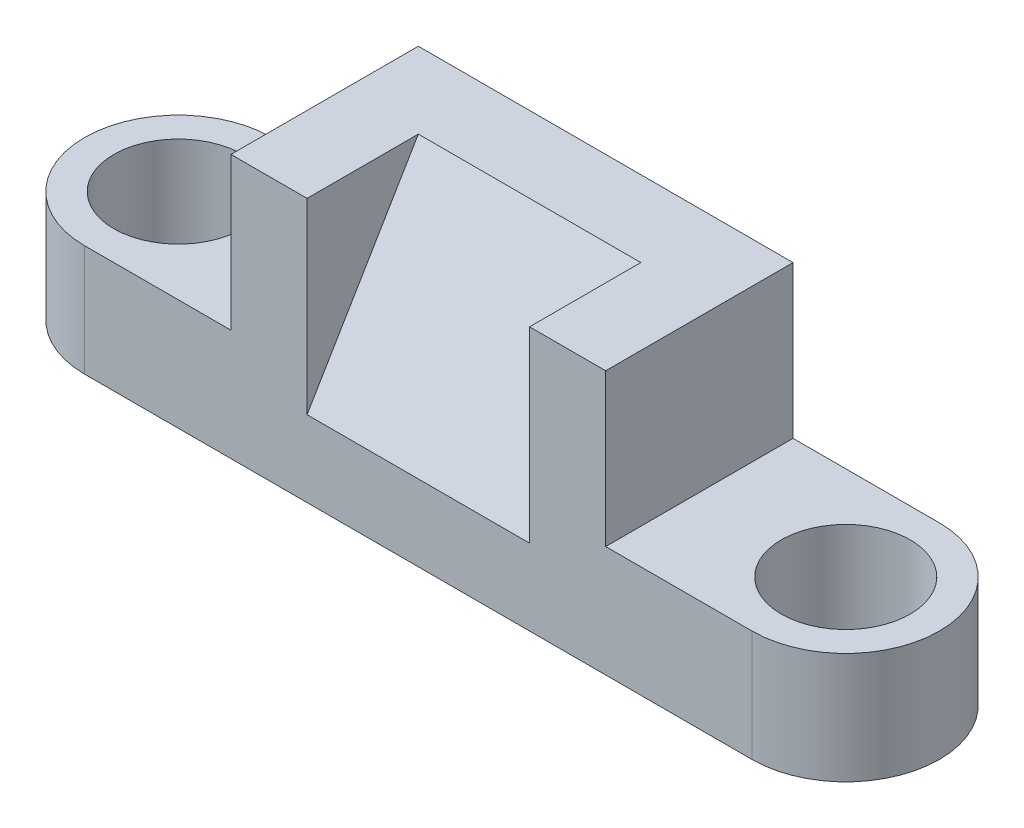
SolidWorks part; units mm, degrees
ref_plane "Front Plane" through (0, 0, 0) normal (0, 0, 1) x (1, 0, 0)
ref_plane "Top Plane" through (0, 0, 0) normal (0, 1, 0) x (1, 0, 0)
ref_plane "Right Plane" through (0, 0, 0) normal (1, 0, 0) x (0, 0, -1)
sketch "Sketch2" plane through (0, 0, 0) normal (0, 1, 0) x (1, 0, 0)
  line L1 (0, 0) -> (64, 0)
  line L2 (0, 0) -> (0, 64)
  line L3 (0, 64) -> (64, 64)
  line L4 (64, 0) -> (64, 64)
  dimension "D1" = 64
  dimension "D2" = 64
extrude "Boss-Extrude1" add sketch "Sketch2" along normal blind 45
sketch "Sketch3" plane through (0, 0, 0) normal (0, 1, 0) x (1, 0, 0)
  line L0 (0, 32) -> (-25, 32) construction
  line L1 (0, 64) -> (0, 0) construction
  line L2 (64, 32) -> (89, 32) construction
  line L3 (64, 0) -> (64, 64) construction
  line L4 (-25, 48) -> (0, 48)
  line L5 (-25, 16) -> (0, 16)
  line L6 (89, 48) -> (64, 48)
  line L7 (89, 16) -> (64, 16)
  line L8 (0, 48) -> (0, 16)
  line L9 (64, 48) -> (64, 16)
  circle A0 centre (-25, 32) radius 11
  circle A1 centre (89, 32) radius 11
  arc A2 (-25, 48) -> (-25, 16) centre (-25, 32) ccw
  arc A3 (89, 16) -> (89, 48) centre (89, 32) ccw
  dimension "D2" = 22
  dimension "D3" = 25
  dimension "D4" = 22
  dimension "D5" = 32
  dimension "D6" = 32
  dimension "D1" = 114
  dimension "D7" = 25
  dimension "D8" = 25
  dimension "D9" = 32
extrude "Boss-Extrude2" add sketch "Sketch3" along normal blind 19
sketch "Sketch7" plane through (0, 0, 0) normal (-1, 0, 0) x (0, 0, 1)
  line L0 (-16, 0) -> (-16, 45)
  line L1 (-64, 45) -> (0, 45) construction
  line L2 (-16, 45) -> (0, 45)
  line L3 (0, 45) -> (0, 0)
  line L4 (0, 0) -> (-16, 0)
extrude "Cut-Extrude2" cut sketch "Sketch7" against normal blind 148
sketch "Sketch9" plane through (0, 45, 0) normal (0, 1, 0) x (1, 0, 0)
  line L0 (0, 48) -> (64, 48)
  line L1 (0, 48) -> (0, 64)
  line L2 (0, 64) -> (64, 64)
  line L3 (64, 64) -> (64, 48)
extrude "Cut-Extrude4" cut sketch "Sketch9" against normal blind 148
sketch "Sketch10" plane through (0, 45, 0) normal (0, 1, 0) x (1, 0, 0)
  line L0 (64, 16) -> (0, 16) construction
  line L1 (13, 16) -> (51, 16)
  line L2 (13, 16) -> (13, 35)
  line L3 (13, 35) -> (51, 35)
  line L4 (51, 16) -> (51, 35)
  line L5 (0, 48) -> (64, 48) construction
  line L6 (64, 16) -> (64, 48) construction
  line L7 (0, 48) -> (0, 16) construction
  point P6 (32, 35)
  dimension "D1" = 13
  dimension "D2" = 13
  dimension "D3" = 13
extrude "Cut-Extrude5" cut sketch "Sketch10" against normal blind 32
sketch "Sketch12" plane through (51, 0, 0) normal (-1, 0, 0) x (0, 0, 1)
  line L0 (-35, 45) -> (-16, 13)
  line L1 (-16, 13) -> (-35, 13)
  line L2 (-35, 13) -> (-35, 45)
extrude "Boss-Extrude4" add sketch "Sketch12" along normal blind 42
